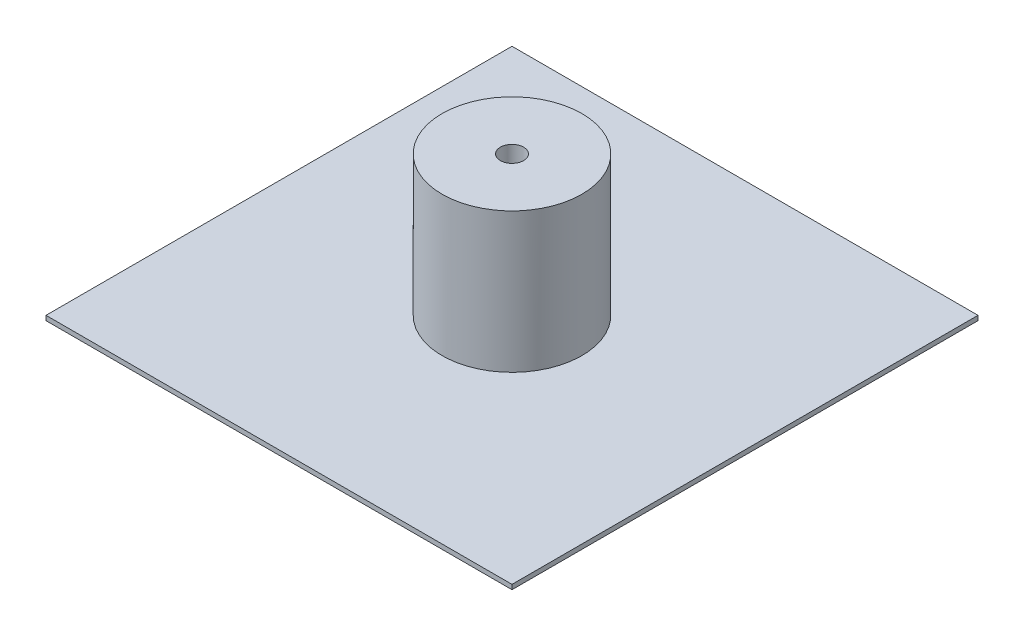
SolidWorks part; units mm, degrees
ref_plane "Front Plane" through (0, 0, 0) normal (0, 0, 1) x (1, 0, 0)
ref_plane "Top Plane" through (0, 0, 0) normal (0, 1, 0) x (1, 0, 0)
ref_plane "Right Plane" through (0, 0, 0) normal (1, 0, 0) x (0, 0, -1)
sketch "Sketch1" plane through (0, 0, 0) normal (0, 1, 0) x (1, 0, 0)
  line L1 (-500, -500) -> (500, -500)
  line L2 (-500, -500) -> (-500, 500)
  line L3 (-500, 500) -> (500, 500)
  line L4 (500, -500) -> (500, 500)
  line L5 (-500, -500) -> (500, 500) construction
  line L6 (-500, 500) -> (500, -500) construction
  point P0 (0, 0)
  dimension "D1" = 1000
  dimension "D2" = 1000
extrude "Boss-Extrude1" add sketch "Sketch1" along normal blind 10
sketch "Sketch2" plane through (0, 10, 0) normal (0, 1, 0) x (1, 0, 0)
  circle A0 centre (0, 0) radius 150
  dimension "D1" = 300
extrude "Boss-Extrude2" add sketch "Sketch2" along normal blind 300
sketch "Sketch3" plane through (0, 310, 0) normal (0, 1, 0) x (1, 0, 0)
  circle A0 centre (0, 0) radius 25
  dimension "D1" = 50
extrude "Cut-Extrude1" cut sketch "Sketch3" against normal blind 50
